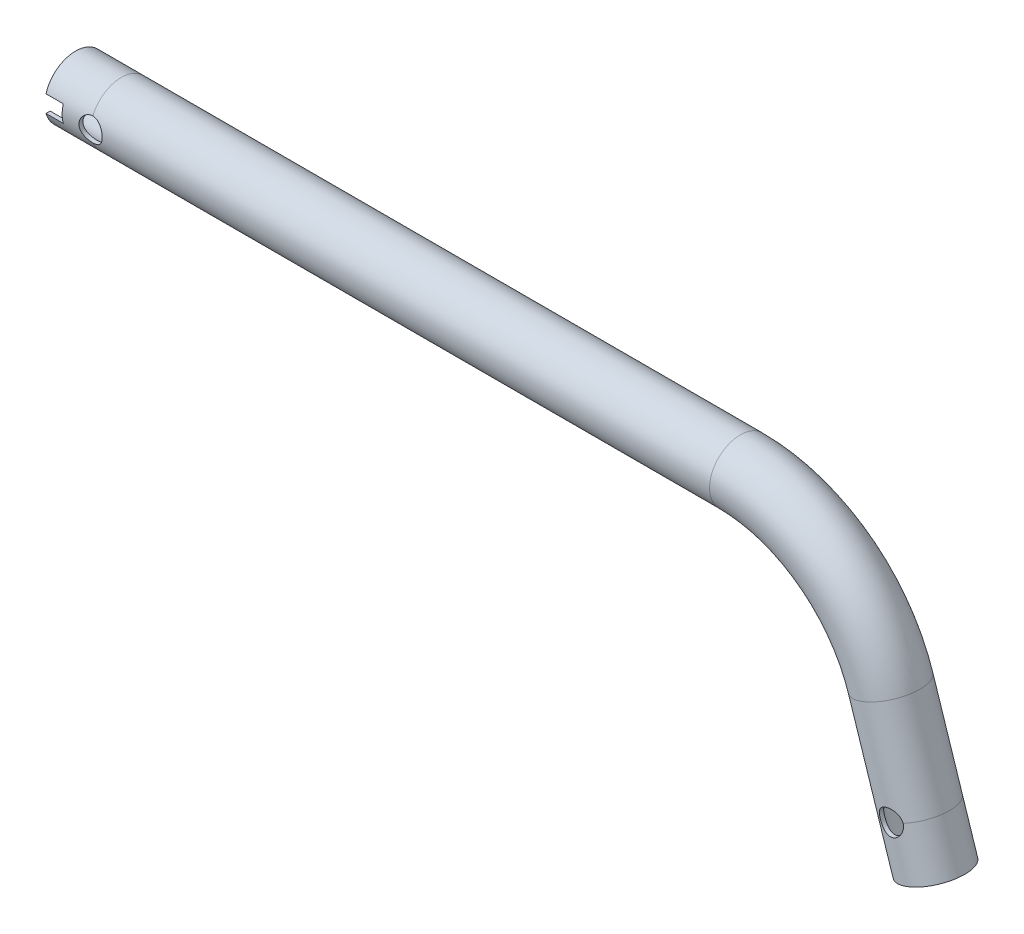
SolidWorks part; units mm, degrees
ref_plane "Front Plane" through (0, 0, 0) normal (0, 0, 1) x (1, 0, 0)
ref_plane "Top Plane" through (0, 0, 0) normal (0, 1, 0) x (1, 0, 0)
ref_plane "Right Plane" through (0, 0, 0) normal (1, 0, 0) x (0, 0, -1)
sketch "Sketch1" plane through (0, 0, 0) normal (0, 0, 1) x (1, 0, 0)
  line L0 (0, 0) -> (185.994, 0)
  line L1 (231.1692, -32.8217) -> (240, -60)
  line L2 (0, 0) -> (-13.7387, 0)
  line L3 (240, -60) -> (244.6353, -74.2658)
  arc A0 (231.1692, -32.8217) -> (185.994, 0) centre (185.994, -47.5) ccw
  point P10 (240, -60)
  dimension "D2" = 47.5
  dimension "D5" = 303
  dimension "D1" = 72
  dimension "D3" = 240
  dimension "D4" = 60
  dimension "D6" = 15
ref_plane "Plane1" through (-13.7387, 0, 0) normal (-1, 0, 0) x (0, 0, 1)
sketch "Sketch2" plane through (-13.7387, 0, 0) normal (-1, 0, 0) x (0, 0, 1)
  circle A0 centre (0, 0) radius 9.25
  circle A1 centre (0, 0) radius 8.05
  dimension "D1" = 1.2
  dimension "D2" = 18.5
sweep "Sweep1" add profiles "Sketch2" path "Sketch1"
sketch "Sketch3" plane through (0, 0, 0) normal (0, 0, 1) x (1, 0, 0)
  line L0 (231.2027, -62.8584) -> (248.7973, -57.1416) construction
  circle A4 centre (240, -60) radius 3.6
  point P2 (0, 0)
  point P3 (240, -50)
extrude "Cut-Extrude1" cut sketch "Sketch3" against normal up to next and the other way up to next
sketch "Sketch4" plane through (0, 0, 0) normal (0, 0, 1) x (1, 0, 0)
  line L0 (0, -9.25) -> (0, 9.25) construction
  circle A0 centre (0, 0) radius 3.5
  dimension "D1" = 7
extrude "Cut-Extrude2" cut sketch "Sketch4" along normal up to next
sketch "Sketch5" plane through (0, 0, 0) normal (0, 0, 1) x (1, 0, 0)
  line L0 (-13.7387, 0) -> (-13.7387, 2.555)
  line L1 (-13.7387, 9.25) -> (-13.7387, -9.25) construction
  line L2 (-13.7387, 2.555) -> (-8.5387, 2.555)
  line L3 (-8.5387, 2.555) -> (-8.5387, -2.555)
  line L4 (-8.5387, -2.555) -> (-13.7387, -2.555)
  line L5 (-13.7387, -2.555) -> (-13.7387, 0)
  dimension "D1" = 5.2
  dimension "D2" = 5.11
extrude "Cut-Extrude3" cut sketch "Sketch5" against normal through all and the other way through all
